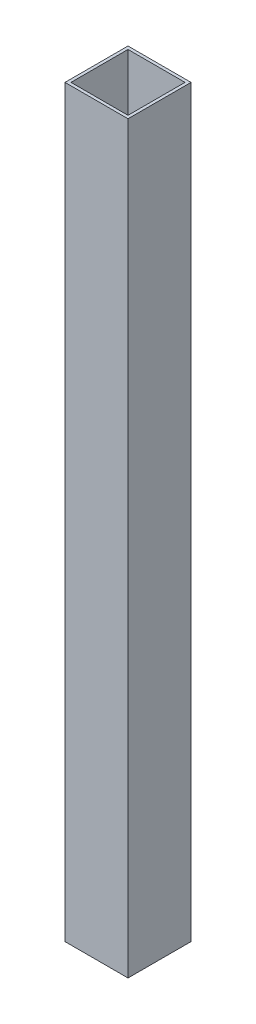
SolidWorks part; units mm, degrees
ref_plane "Front Plane" through (0, 0, 0) normal (0, 0, 1) x (1, 0, 0)
ref_plane "Top Plane" through (0, 0, 0) normal (0, 1, 0) x (1, 0, 0)
ref_plane "Right Plane" through (0, 0, 0) normal (1, 0, 0) x (0, 0, -1)
sketch "Sketch2" plane through (0, 0, 0) normal (0, 1, 0) x (1, 0, 0)
  line L0 (-11.5, 11.5) -> (11.5, 11.5)
  line L1 (-12.7, -12.7) -> (12.7, -12.7)
  line L2 (-12.7, -12.7) -> (-12.7, 12.7)
  line L3 (-12.7, 12.7) -> (12.7, 12.7)
  line L4 (12.7, -12.7) -> (12.7, 12.7)
  line L5 (-12.7, -12.7) -> (12.7, 12.7) construction
  line L6 (-12.7, 12.7) -> (12.7, -12.7) construction
  line L7 (11.5, -11.5) -> (11.5, 11.5)
  line L8 (-11.5, -11.5) -> (11.5, -11.5)
  line L9 (-11.5, -11.5) -> (-11.5, 11.5)
  point P0 (0, 0)
  dimension "D1" = 25.4
  dimension "D3" = 1.2
extrude "Boss-Extrude1" add sketch "Sketch2" along normal mid plane 300
